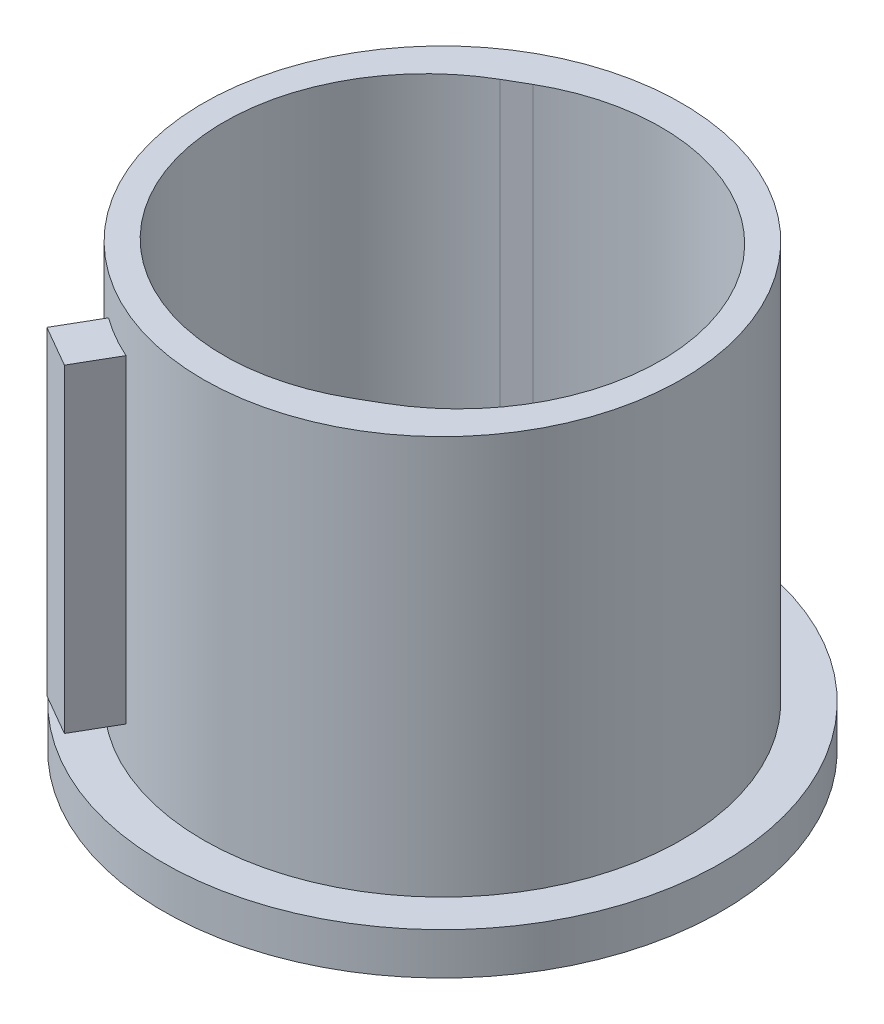
SolidWorks part; units mm, degrees
other "Acetal Torque Guide Bush Relieved"
other "Acetal Torque Guide Bush Relieved Left"
ref_plane "Front Plane" through (0, 0, 0) normal (0, 0, 1) x (1, 0, 0)
ref_plane "Top Plane" through (0, 0, 0) normal (0, 1, 0) x (1, 0, 0)
ref_plane "Right Plane" through (0, 0, 0) normal (1, 0, 0) x (0, 0, -1)
sketch3d "Guide bush barrel sketch datum points"
  point P0 (-20.2917, -105.98, 0)
  point P1 (-10.2917, -105.98, 0)
  point P2 (-20.2917, -105.98, -10)
ref_plane "Guide bush barrel sketch plane" through (0, -105.98, 0) normal (0, 1, 0) x (1, 0, 0)
sketch "Guide bush barrel sketch" plane through (0, -105.98, 0) normal (0, 1, 0) x (1, 0, 0)
  circle A0 centre (-20.2917, 0) radius 6
extrude "Guide bush barrel" add sketch "Guide bush barrel sketch" along normal blind 10 separate body
sketch3d "Guide bush flange sketch datum points"
  point P0 (-20.2917, -95.98, 0)
  point P1 (-10.2917, -95.98, 0)
  point P2 (-20.2917, -95.98, -10)
ref_plane "Guide bush flange sketch plane" through (0, -95.98, 0) normal (0, 1, 0) x (1, 0, 0)
sketch "Guide bush flange sketch" plane through (0, -95.98, 0) normal (0, 1, 0) x (1, 0, 0)
  circle A0 centre (-20.2917, 0) radius 7
extrude "Guide bush flange" add sketch "Guide bush flange sketch" along normal blind 1.05
sketch3d "Directional running slot sketch datum points"
  point P0 (-20.2917, -106.08, 0)
  point P1 (-10.2917, -106.08, 0)
  point P2 (-20.2917, -106.08, -10)
ref_plane "Directional running slot sketch plane" through (0, -106.08, 0) normal (0, 1, 0) x (1, 0, 0)
sketch "Directional running slot sketch" plane through (0, -106.08, 0) normal (0, 1, 0) x (1, 0, 0)
  line L0 (-23.0865, -4.2407) -> (-22.5668, -4.5407)
  line L1 (-17.4968, 4.2407) -> (-18.0165, 4.5407)
  arc A0 (-22.5668, -4.5407) -> (-17.4968, 4.2407) centre (-20.0318, -0.15) ccw
  arc A1 (-18.0165, 4.5407) -> (-23.0865, -4.2407) centre (-20.5515, 0.15) ccw
extrude "Directional running slot" cut sketch "Directional running slot sketch" along normal blind 11.25
sketch3d "Antirotation guide key sketch datum points"
  point P0 (-20.2917, -105, 0)
  point P1 (-10.2917, -105, 0)
  point P2 (-20.2917, -105, -10)
ref_plane "Antirotation guide key sketch plane" through (0, -105, 0) normal (0, 1, 0) x (1, 0, 0)
sketch "Antirotation guide key sketch" plane through (0, -105, 0) normal (0, 1, 0) x (1, 0, 0)
  line L0 (-14.4917, -0.6) -> (-13.1917, -0.6)
  line L1 (-13.1917, -0.6) -> (-13.1917, 0.6)
  line L2 (-13.1917, 0.6) -> (-14.4917, 0.6)
  line L3 (-14.4917, 0.6) -> (-14.4917, -0.6)
extrude "Antirotation guide key" add sketch "Antirotation guide key sketch" along normal blind 8
move or copy body "Move1" bodies to move or copy 104 copy no translate (56.2917, 0, 0) parameters "D1"=56.2917, "D2"=0, "D3"=0
move or copy body "Move2" bodies to move or copy 105 copy no rotation origin (0, 0, 0) rotation axis (0, -1, 0) rotation angle 120
move or copy body "Move3" bodies to move or copy 106 copy no translate (-56.2917, 0, 0) parameters "D1"=56.2917, "D2"=0, "D3"=0
sketch3d "Mirror1 profile datum points"
  point P0 (0, 0, 0)
  point P1 (10, 0, 0)
  point P2 (0, 0, 10)
ref_plane "Mirror1 profile plane" through (0, 0, 0) normal (0, -1, 0) x (-1, 0, 0)
mirror "Mirror1" about plane through (0, 0, 0) normal (0, -1, 0) of bodies 107
delete or keep bodies "Remove1" type delete bodies bodies 107
